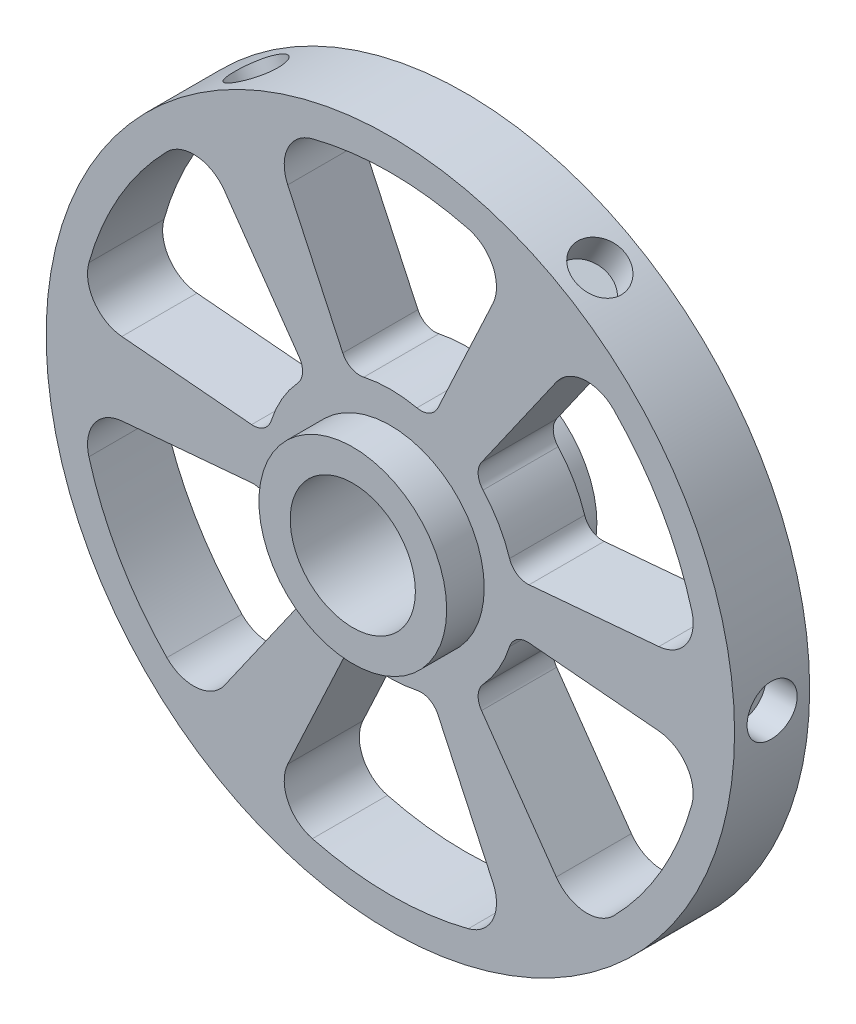
SolidWorks part; units mm, degrees
ref_plane "Alzado" through (0, 0, 0) normal (0, 0, 1) x (1, 0, 0)
ref_plane "Planta" through (0, 0, 0) normal (0, 1, 0) x (1, 0, 0)
ref_plane "Vista lateral" through (0, 0, 0) normal (1, 0, 0) x (0, 0, -1)
sketch "Croquis1" plane through (0, 0, 0) normal (0, 0, 1) x (1, 0, 0)
  circle A0 centre (0, 0) radius 10
  circle A1 centre (0, 0) radius 15
  dimension "D1" = 20
  dimension "D2" = 30
extrude "Saliente-Extruir1" add sketch "Croquis1" along normal mid plane 24
sketch "Croquis2" plane through (0, 0, 0) normal (0, 0, 1) x (1, 0, 0)
  line L0 (0, 96.0012) -> (0, -87.2218) construction
  line L1 (-16.396, 40.0779) -> (-7.5972, 21.2088)
  line L2 (16.396, 40.0779) -> (7.5972, 21.2088)
  line L3 (42.9065, 5.8396) -> (22.166, 4.025)
  line L4 (26.5105, 34.2383) -> (14.5688, 17.1838)
  line L5 (26.5105, -34.2383) -> (14.5688, -17.1838)
  line L6 (42.9065, -5.8396) -> (22.166, -4.025)
  line L7 (-16.396, -40.0779) -> (-7.5972, -21.2088)
  line L8 (16.396, -40.0779) -> (7.5972, -21.2088)
  line L9 (-42.9065, -5.8396) -> (-22.166, -4.025)
  line L10 (-26.5105, -34.2383) -> (-14.5688, -17.1838)
  line L11 (-26.5105, 34.2383) -> (-14.5688, 17.1838)
  line L12 (-42.9065, 5.8396) -> (-22.166, 4.025)
  circle A0 centre (0, 0) radius 55
  arc A1 (12.4524, 48.4245) -> (-12.4524, 48.4245) centre (0, 0) ccw
  arc A2 (4.242, 19.545) -> (-4.242, 19.545) centre (0, 0) ccw
  circle A3 centre (0, 0) radius 15
  arc A4 (16.396, 40.0779) -> (12.4524, 48.4245) centre (10.9581, 42.6136) ccw
  arc A5 (-16.396, 40.0779) -> (-12.4524, 48.4245) centre (-10.9581, 42.6136) cw
  arc A6 (7.5972, 21.2088) -> (4.242, 19.545) centre (4.8783, 22.4767) cw
  arc A7 (-7.5972, 21.2088) -> (-4.242, 19.545) centre (-4.8783, 22.4767) ccw
  arc A8 (22.166, 4.025) -> (19.0474, 6.0988) centre (21.9045, 7.0136) cw
  arc A9 (42.9065, 5.8396) -> (48.1631, 13.4281) centre (42.3835, 11.8168) ccw
  arc A10 (19.0474, 6.0988) -> (14.8054, 13.4462) centre (0, 0) ccw
  arc A11 (14.5688, 17.1838) -> (14.8054, 13.4462) centre (17.0262, 15.4631) ccw
  arc A12 (26.5105, 34.2383) -> (35.7107, 34.9964) centre (31.4254, 30.7968) cw
  arc A13 (48.1631, 13.4281) -> (35.7107, 34.9964) centre (0, 0) ccw
  arc A14 (14.5688, -17.1838) -> (14.8054, -13.4462) centre (17.0262, -15.4631) cw
  arc A15 (26.5105, -34.2383) -> (35.7107, -34.9964) centre (31.4254, -30.7968) ccw
  arc A16 (14.8054, -13.4462) -> (19.0474, -6.0988) centre (0, 0) ccw
  arc A17 (22.166, -4.025) -> (19.0474, -6.0988) centre (21.9045, -7.0136) ccw
  arc A18 (42.9065, -5.8396) -> (48.1631, -13.4281) centre (42.3835, -11.8168) cw
  arc A19 (35.7107, -34.9964) -> (48.1631, -13.4281) centre (0, 0) ccw
  arc A20 (-7.5972, -21.2088) -> (-4.242, -19.545) centre (-4.8783, -22.4767) cw
  arc A21 (-16.396, -40.0779) -> (-12.4524, -48.4245) centre (-10.9581, -42.6136) ccw
  arc A22 (-4.242, -19.545) -> (4.242, -19.545) centre (0, 0) ccw
  arc A23 (7.5972, -21.2088) -> (4.242, -19.545) centre (4.8783, -22.4767) ccw
  arc A24 (16.396, -40.0779) -> (12.4524, -48.4245) centre (10.9581, -42.6136) cw
  arc A25 (-12.4524, -48.4245) -> (12.4524, -48.4245) centre (0, 0) ccw
  arc A26 (-22.166, -4.025) -> (-19.0474, -6.0988) centre (-21.9045, -7.0136) cw
  arc A27 (-42.9065, -5.8396) -> (-48.1631, -13.4281) centre (-42.3835, -11.8168) ccw
  arc A28 (-19.0474, -6.0988) -> (-14.8054, -13.4462) centre (0, 0) ccw
  arc A29 (-14.5688, -17.1838) -> (-14.8054, -13.4462) centre (-17.0262, -15.4631) ccw
  arc A30 (-26.5105, -34.2383) -> (-35.7107, -34.9964) centre (-31.4254, -30.7968) cw
  arc A31 (-48.1631, -13.4281) -> (-35.7107, -34.9964) centre (0, 0) ccw
  arc A32 (-14.5688, 17.1838) -> (-14.8054, 13.4462) centre (-17.0262, 15.4631) cw
  arc A33 (-26.5105, 34.2383) -> (-35.7107, 34.9964) centre (-31.4254, 30.7968) ccw
  arc A34 (-14.8054, 13.4462) -> (-19.0474, 6.0988) centre (0, 0) ccw
  arc A35 (-22.166, 4.025) -> (-19.0474, 6.0988) centre (-21.9045, 7.0136) ccw
  arc A36 (-42.9065, 5.8396) -> (-48.1631, 13.4281) centre (-42.3835, 11.8168) cw
  arc A37 (-35.7107, 34.9964) -> (-48.1631, 13.4281) centre (0, 0) ccw
  point P12 (19.2295, 46.1544)
  point P15 (-19.2295, 46.1544)
  point P18 (6.5235, 18.9062)
  point P21 (-6.5235, 18.9062)
  point P85 (0, 0)
  dimension "D1" = 110
  dimension "D2" = 100
  dimension "D3" = 40
  dimension "D5" = 6
  dimension "D6" = 3
  dimension "D4" = 25
  dimension "D7" = 6
extrude "Saliente-Extruir2" add sketch "Croquis2" along normal mid plane 12
ref_plane "Plano2" through (55, 0, 0) normal (1, 0, 0) x (0, 0, -1)
sketch "Croquis4" plane through (55, 0, 0) normal (1, 0, 0) x (0, 0, -1)
  circle A0 centre (0, 0) radius 4
  dimension "D1" = 8
extrude "Cortar-Extruir2" cut sketch "Croquis4" against normal blind 5
pattern_circular "MatrizC1" count 6 over 360 about axis through (0, 0, 0) along (0, 0, 1) of "Cortar-Extruir2"
